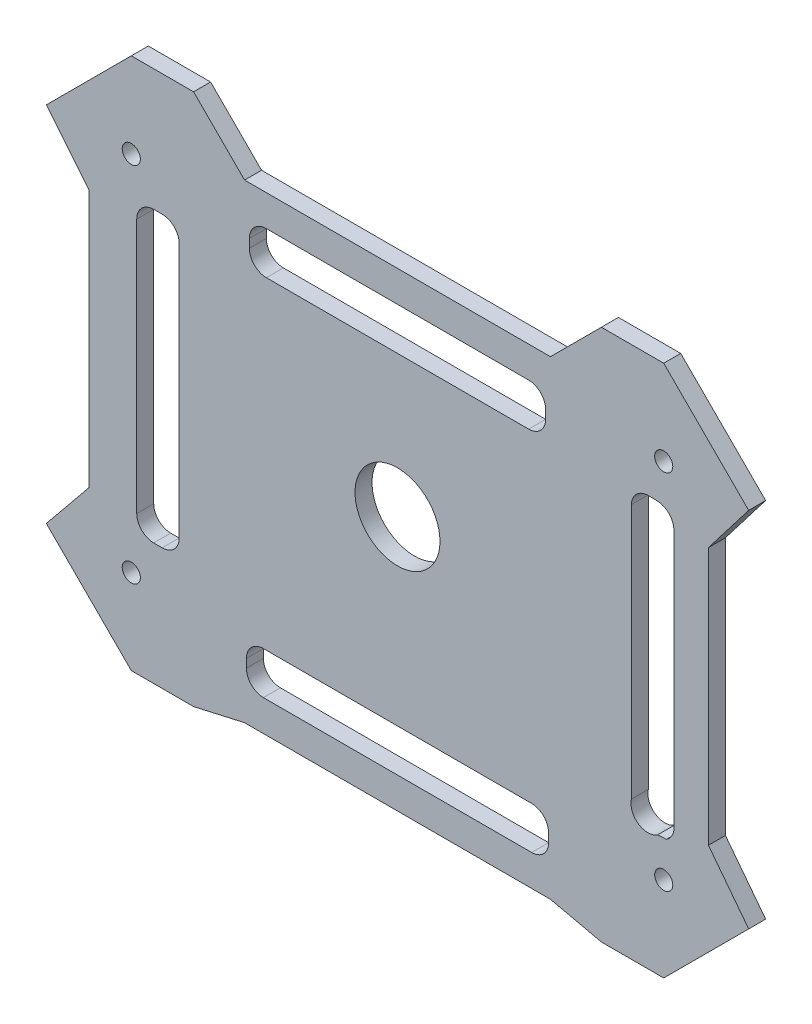
SolidWorks part; units mm, degrees
ref_plane "Front Plane" through (0, 0, 0) normal (0, 0, 1) x (1, 0, 0)
ref_plane "Top Plane" through (0, 0, 0) normal (0, 1, 0) x (1, 0, 0)
ref_plane "Right Plane" through (0, 0, 0) normal (1, 0, 0) x (0, 0, -1)
sketch "Sketch1" plane through (0, 0, 0) normal (0, 0, 1) x (1, 0, 0)
  line L0 (-66.8992, 56.7884) -> (-51.8992, 71.7884)
  line L1 (-31.8992, 62.7884) -> (22.1008, 62.7884)
  line L2 (49.9991, 47.5467) -> (49.9991, 2.0302)
  line L3 (-66.8992, -7.2116) -> (-59.3714, 2.0302)
  line L4 (-40.8992, 71.7884) -> (-31.8992, 62.7884)
  line L5 (-51.8992, 71.7884) -> (-40.8992, 71.7884)
  line L6 (42.1008, 71.7884) -> (57.1008, 56.7884)
  line L7 (-66.8992, -7.2116) -> (-51.8992, -22.2116)
  line L8 (-51.8992, -22.2116) -> (-40.8992, -22.2116)
  line L9 (42.1008, -22.2116) -> (57.1008, -7.2116)
  line L10 (31.1008, -22.2116) -> (42.1008, -22.2116)
  line L11 (31.1008, 71.7884) -> (42.1008, 71.7884)
  line L12 (-59.3714, 47.5467) -> (-66.8992, 56.7884)
  line L14 (22.1008, -20.1806) -> (-31.8992, -20.1806)
  line L15 (49.9991, 47.5467) -> (57.1008, 56.7884)
  line L16 (49.9991, 2.0302) -> (57.1008, -7.2116)
  line L17 (22.1008, 62.7884) -> (31.1008, 71.7884)
  line L18 (-31.8992, -20.1806) -> (-40.8992, -22.2116)
  line L19 (22.1008, -20.1806) -> (31.1008, -22.2116)
  line L20 (-47.9434, 50.2936) -> (-46.4434, 50.2962)
  line L21 (-50.9383, 47.2885) -> (-50.9383, 2.2885)
  line L22 (-47.9383, -0.7115) -> (-46.4383, -0.7115)
  line L23 (-43.4383, 47.2962) -> (-43.4383, 2.3013)
  line L24 (-28.0547, 57.2884) -> (18.2562, 57.2884)
  line L25 (-31.0547, 54.2884) -> (-31.0547, 52.7884)
  line L26 (-28.0547, 49.7884) -> (18.2562, 49.7884)
  line L27 (21.2562, 54.2884) -> (21.2562, 52.7884)
  line L28 (40.9864, 50.1522) -> (39.4872, 50.2014)
  line L29 (43.8905, 47.3013) -> (43.8905, 2.3013)
  line L30 (42.5533, -0.7853) -> (41.0541, -0.8344)
  line L31 (36.3905, 47.3013) -> (36.3905, 2.2962)
  line L32 (18.7783, -14.6806) -> (-28.5767, -14.6806)
  line L33 (21.7783, -11.6806) -> (21.7783, -10.1806)
  line L34 (18.7783, -7.1806) -> (-28.5767, -7.1806)
  line L35 (-31.5767, -11.6806) -> (-31.5767, -10.1806)
  line L36 (-59.3714, 47.5467) -> (-59.3714, 2.0302)
  line L37 (-51.8992, 56.7884) -> (42.1008, 56.7884) construction
  line L38 (42.1008, 56.7884) -> (42.1008, -7.2116) construction
  line L39 (42.1008, -7.2116) -> (-51.8992, -7.2116) construction
  line L40 (-51.8992, -7.2116) -> (-51.8992, 56.7884) construction
  arc A0 (42.5533, -0.7853) -> (43.8905, 2.3013) centre (40.9424, 1.7456) ccw
  arc A1 (36.3905, 2.2962) -> (41.0541, -0.8344) centre (39.3102, 1.6067) ccw
  arc A2 (43.8905, 47.3013) -> (40.9864, 50.1522) centre (40.8942, 47.1536) ccw
  arc A3 (39.4872, 50.2014) -> (36.3905, 47.3013) centre (39.3889, 47.203) ccw
  arc A4 (18.2562, 49.7884) -> (21.2562, 52.7884) centre (18.2562, 52.7884) ccw
  arc A5 (21.2562, 54.2884) -> (18.2562, 57.2884) centre (18.2562, 54.2884) ccw
  arc A6 (-31.0547, 52.7884) -> (-28.0547, 49.7884) centre (-28.0547, 52.7884) ccw
  arc A7 (-28.0547, 57.2884) -> (-31.0547, 54.2884) centre (-28.0547, 54.2884) ccw
  arc A8 (-43.4383, 47.2962) -> (-46.4434, 50.2962) centre (-46.4383, 47.2962) ccw
  arc A9 (-47.9434, 50.2936) -> (-50.9383, 47.2885) centre (-47.9383, 47.2936) ccw
  arc A10 (-46.4383, -0.7115) -> (-43.4383, 2.3013) centre (-46.4383, 2.2885) ccw
  arc A11 (-50.9383, 2.2885) -> (-47.9383, -0.7115) centre (-47.9383, 2.2885) ccw
  circle A12 centre (-4.8992, 24.7987) radius 7.5
  arc A13 (18.7783, -14.6806) -> (21.7783, -11.6806) centre (18.7783, -11.6806) ccw
  arc A14 (21.7783, -10.1806) -> (18.7783, -7.1806) centre (18.7783, -10.1806) ccw
  arc A15 (-28.5767, -7.1806) -> (-31.5767, -10.1806) centre (-28.5767, -10.1806) ccw
  arc A16 (-31.5767, -11.6806) -> (-28.5767, -14.6806) centre (-28.5767, -11.6806) ccw
  circle A17 centre (-51.8992, 56.7884) radius 1.6
  circle A18 centre (42.1008, 56.7884) radius 1.6
  circle A19 centre (42.1008, -7.2116) radius 1.6
  circle A20 centre (-51.8992, -7.2116) radius 1.6
  point P78 (0, 0)
  point P79 (49.4294, 47.5467)
  point P80 (0, 0)
  point P90 (-4.8992, 62.7884)
  point P94 (-4.8992, 57.2884)
  point P95 (-4.8992, -7.1806)
  point P96 (-4.8992, 49.7884)
  point P99 (36.3905, 24.7987)
  point P103 (-43.4383, 24.7987)
  dimension "D10" = 94
extrude "Boss-Extrude1" add sketch "Sketch1" along normal blind 3
